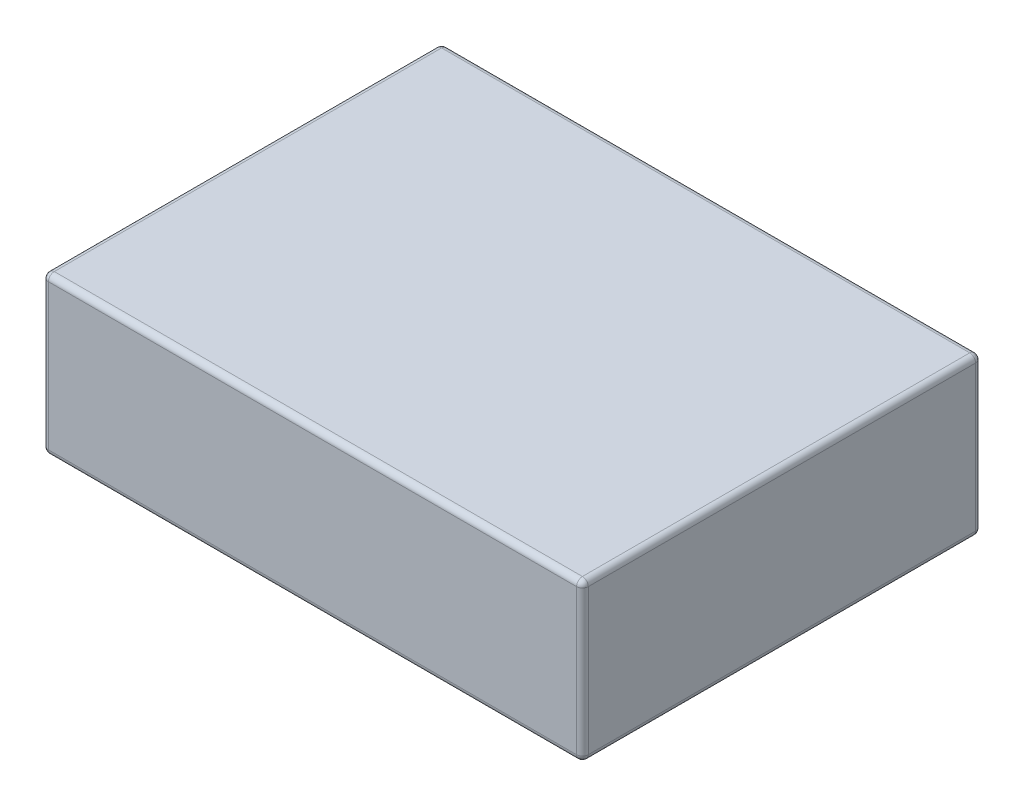
SolidWorks part; units mm, degrees
material "Custom Plastic"
ref_plane "Front Plane" through (0, 0, 0) normal (0, 0, 1) x (1, 0, 0)
ref_plane "Top Plane" through (0, 0, 0) normal (0, 1, 0) x (1, 0, 0)
ref_plane "Right Plane" through (0, 0, 0) normal (1, 0, 0) x (0, 0, -1)
sketch "Sketch1" plane through (0, 0, 0) normal (0, 1, 0) x (1, 0, 0)
  line L1 (0, 0) -> (23, 0)
  line L2 (0, 0) -> (0, 17)
  line L3 (0, 17) -> (23, 17)
  line L4 (23, 0) -> (23, 17)
  dimension "D1" = 17
  dimension "D2" = 23
extrude "Boss-Extrude1" add sketch "Sketch1" along normal blind 6.7
fillet "Fillet1" radius 0.25 12 edges at (0, 0, -8.5) (0, 3.35, -17) (11.5, 0, -17) (23, 3.35, -17) (23, 0, -8.5) (23, 3.35, 0) (11.5, 0, 0) (0, 3.35, 0) (0, 6.7, -8.5) (11.5, 6.7, -17) (23, 6.7, -8.5) (11.5, 6.7, 0)
